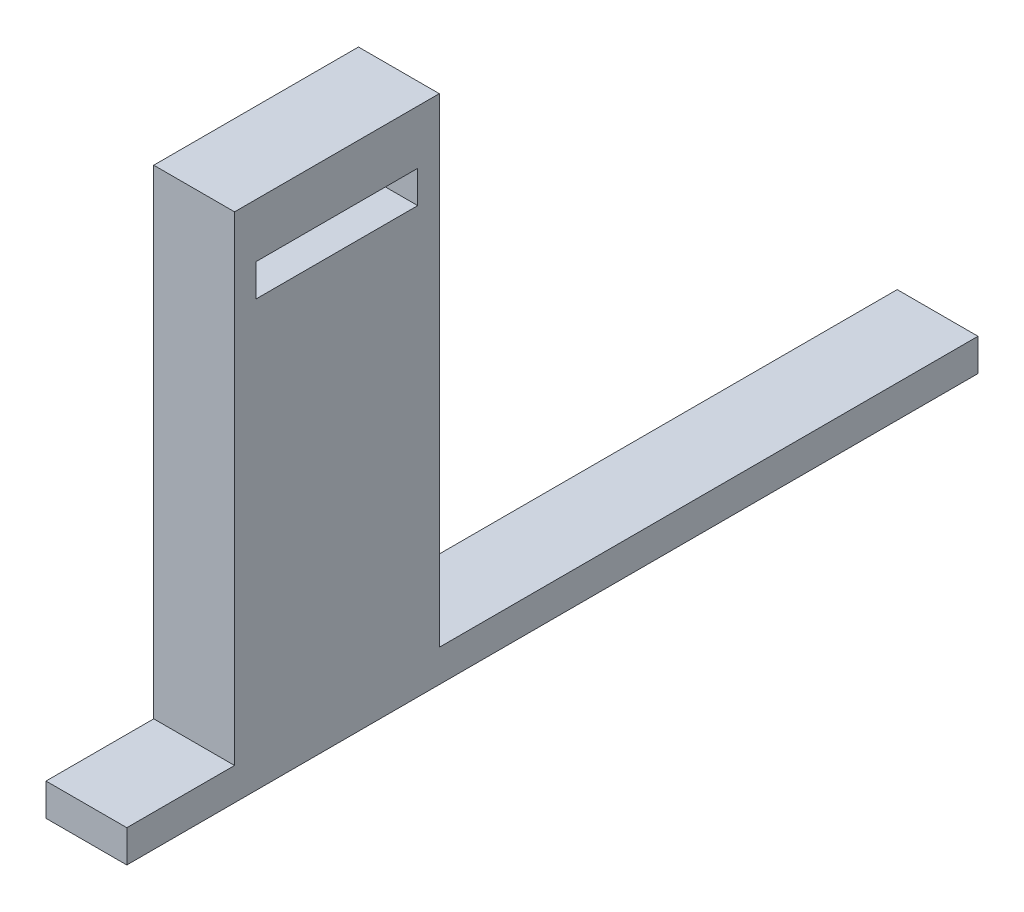
SolidWorks part; units mm, degrees
ref_plane "Front Plane" through (0, 0, 0) normal (0, 0, 1) x (1, 0, 0)
ref_plane "Top Plane" through (0, 0, 0) normal (0, 1, 0) x (1, 0, 0)
ref_plane "Right Plane" through (0, 0, 0) normal (1, 0, 0) x (0, 0, -1)
sketch "Sketch1" plane through (0, 0, 0) normal (1, 0, 0) x (0, 0, -1)
  line L0 (-79, 0) -> (79, 0)
  line L1 (-79, 0) -> (-79, 6)
  line L2 (-79, 6) -> (-59, 6)
  line L3 (-59, 6) -> (-59, 95)
  line L4 (-59, 95) -> (-21, 95)
  line L5 (-21, 95) -> (-21, 6)
  line L6 (-21, 6) -> (79, 6)
  line L7 (79, 6) -> (79, 0)
  line L9 (-55, 85) -> (-25, 85)
  line L10 (-55, 85) -> (-55, 79)
  line L11 (-55, 79) -> (-25, 79)
  line L12 (-25, 85) -> (-25, 79)
  point P4 (0, 0)
  dimension "D1" = 38
  dimension "D2" = 158
  dimension "D3" = 95
  dimension "D4" = 20
  dimension "D5" = 6
  dimension "D6" = 10
  dimension "D7" = 6
  dimension "D8" = 4
  dimension "D9" = 4
extrude "Boss-Extrude1" add sketch "Sketch1" along normal blind 15
sketch "Sketch2" [suppressed] plane through (0, 0, 0) normal (-1, 0, 0) x (0, 0, 1)
  line L1 (-79, 0) -> (21, 0)
  line L2 (-79, 0) -> (-79, 6)
  line L3 (-79, 6) -> (21, 6)
  line L4 (21, 0) -> (21, 6)
extrude "Boss-Extrude2" [suppressed] add sketch "Sketch2" along normal blind 15
